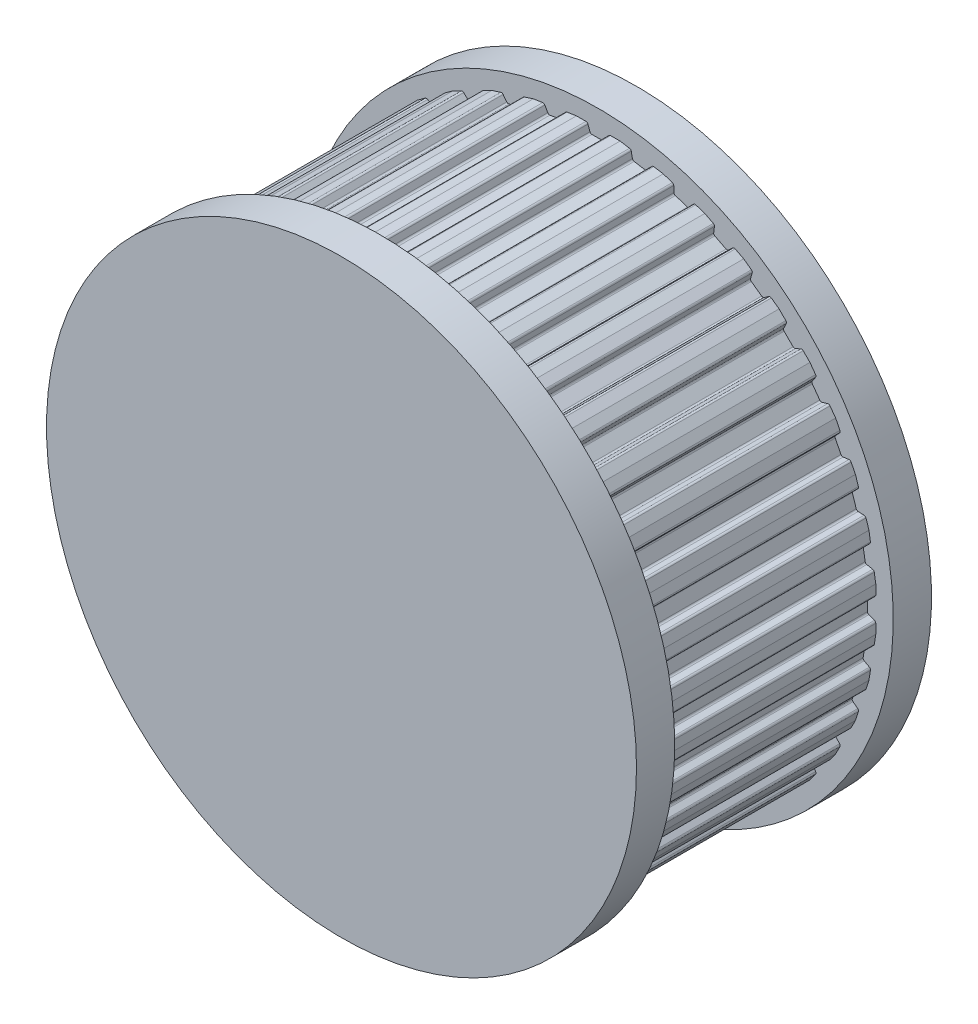
SolidWorks part; units mm, degrees
ref_plane "Front Plane" through (0, 0, 0) normal (0, 0, 1) x (1, 0, 0)
ref_plane "Top Plane" through (0, 0, 0) normal (0, 1, 0) x (1, 0, 0)
ref_plane "Right Plane" through (0, 0, 0) normal (1, 0, 0) x (0, 0, -1)
sketch "Sketch1" plane through (0, 0, 0) normal (0, 0, 1) x (1, 0, 0)
  line L0 (-50.7835, 0) -> (-50.3466, 0)
  line L5 (-50.2571, 0.0627) -> (-50.1641, 0.3183)
  line L6 (-50.0746, 0.381) -> (-49.4934, 0.381)
  line L7 (-49.784, 0.381) -> (-49.784, 0) construction
  line L8 (-49.3109, 0.0627) -> (-49.4039, 0.3183)
  line L39 (-51.2936, 0.1442) -> (-51.3455, 0.4113)
  line L40 (-50.2571, 0.0627) -> (-49.3109, 0.0627) construction
  line L56 (-49.2214, 0) -> (-48.7845, 0)
  line L60 (-51.9981, 0.5781) -> (-51.4241, 0.4872)
  line L61 (-52.2282, 0.2923) -> (-52.0963, 0.5302)
  line L62 (-52.7579, 0.3127) -> (-52.3264, 0.2444)
  line L63 (-51.215, 0.0683) -> (-50.7835, 0)
  line L64 (-53.2392, 0.535) -> (-53.2487, 0.8069)
  line L65 (-53.8671, 1.0737) -> (-53.3144, 0.8941)
  line L66 (-54.1391, 0.8274) -> (-53.9716, 1.0418)
  line L67 (-54.6591, 0.9304) -> (-54.2436, 0.7954)
  line L68 (-53.1734, 0.4477) -> (-52.7579, 0.3127)
  line L69 (-55.0997, 1.2253) -> (-55.0665, 1.4953)
  line L70 (-55.6356, 1.8556) -> (-55.1178, 1.5918)
  line L71 (-55.9428, 1.6549) -> (-55.7438, 1.8404)
  line L72 (-56.4403, 1.838) -> (-56.051, 1.6396)
  line L73 (-55.0484, 1.1288) -> (-54.6591, 0.9304)
  line L74 (-56.8293, 2.1981) -> (-56.7543, 2.4596)
  line L75 (-57.26, 2.9045) -> (-56.7898, 2.5629)
  line L76 (-57.5948, 2.7543) -> (-57.3693, 2.9064)
  line L77 (-58.0575, 3.013) -> (-57.7041, 2.7562)
  line L78 (-56.7937, 2.0948) -> (-56.4403, 1.838)
  line L79 (-58.3854, 3.4295) -> (-58.2704, 3.6761)
  line L80 (-58.7003, 4.1946) -> (-58.2894, 3.7837)
  line L81 (-59.0545, 4.0986) -> (-58.8079, 4.2136)
  line L82 (-59.471, 4.4265) -> (-59.1621, 4.1176)
  line L83 (-58.3664, 3.3219) -> (-58.0575, 3.013)
  line L84 (-59.7297, 4.8892) -> (-59.5776, 5.1147)
  line L85 (-59.9211, 5.6942) -> (-59.5795, 5.224)
  line L86 (-60.2859, 5.6547) -> (-60.0244, 5.7297)
  line L87 (-60.646, 6.0437) -> (-60.3892, 5.6903)
  line L88 (-59.7278, 4.7799) -> (-59.471, 4.4265)
  line L89 (-60.8291, 6.5412) -> (-60.6436, 6.7402)
  line L90 (-60.8922, 7.3662) -> (-60.6284, 6.8484)
  line L91 (-61.2587, 7.3843) -> (-60.9887, 7.4175)
  line L92 (-61.5536, 7.8249) -> (-61.3552, 7.4356)
  line L93 (-60.8444, 6.433) -> (-60.646, 6.0437)
  line L94 (-61.6566, 8.3449) -> (-61.4422, 8.5124)
  line L95 (-61.5899, 9.1696) -> (-61.4103, 8.6169)
  line L96 (-61.949, 9.2448) -> (-61.6771, 9.2353)
  line L97 (-62.1713, 9.7261) -> (-62.0363, 9.3106)
  line L98 (-61.6886, 8.2404) -> (-61.5536, 7.8249)
  line L99 (-62.1917, 10.2558) -> (-61.9538, 10.3877)
  line L100 (-61.9968, 11.0599) -> (-61.9059, 10.4859)
  line L101 (-62.3398, 11.1904) -> (-62.0727, 11.1385)
  line L102 (-62.484, 11.7005) -> (-62.4157, 11.269)
  line L103 (-62.2396, 10.1576) -> (-62.1713, 9.7261)
  line L104 (-62.4213, 12.2269) -> (-62.1657, 12.3199)
  line L105 (-62.103, 12.9906) -> (-62.103, 12.4094)
  line L106 (-62.4213, 13.1731) -> (-62.1657, 13.0801)
  line L107 (-62.484, 13.6995) -> (-62.484, 13.2626)
  line L108 (-62.484, 12.1374) -> (-62.484, 11.7005)
  line L109 (-62.3398, 14.2096) -> (-62.0727, 14.2615)
  line L110 (-61.9059, 14.9141) -> (-61.9968, 14.3401)
  line L111 (-62.1917, 15.1442) -> (-61.9538, 15.0123)
  line L112 (-62.1713, 15.6739) -> (-62.2396, 15.2424)
  line L113 (-62.4157, 14.131) -> (-62.484, 13.6995)
  line L114 (-61.949, 16.1552) -> (-61.6771, 16.1647)
  line L115 (-61.4103, 16.7831) -> (-61.5899, 16.2304)
  line L116 (-61.6566, 17.0551) -> (-61.4422, 16.8876)
  line L117 (-61.5536, 17.5751) -> (-61.6886, 17.1596)
  line L118 (-62.0363, 16.0894) -> (-62.1713, 15.6739)
  line L119 (-61.2587, 18.0157) -> (-60.9887, 17.9825)
  line L120 (-60.6284, 18.5516) -> (-60.8922, 18.0338)
  line L121 (-60.8291, 18.8588) -> (-60.6436, 18.6598)
  line L122 (-60.646, 19.3563) -> (-60.8444, 18.967)
  line L123 (-61.3552, 17.9644) -> (-61.5536, 17.5751)
  line L124 (-60.2859, 19.7453) -> (-60.0244, 19.6703)
  line L125 (-59.5795, 20.176) -> (-59.9211, 19.7058)
  line L126 (-59.7297, 20.5108) -> (-59.5776, 20.2853)
  line L127 (-59.471, 20.9735) -> (-59.7278, 20.6201)
  line L128 (-60.3892, 19.7097) -> (-60.646, 19.3563)
  line L129 (-59.0545, 21.3014) -> (-58.8079, 21.1864)
  line L130 (-58.2894, 21.6163) -> (-58.7003, 21.2054)
  line L131 (-58.3854, 21.9705) -> (-58.2704, 21.7239)
  line L132 (-58.0575, 22.387) -> (-58.3664, 22.0781)
  line L133 (-59.1621, 21.2824) -> (-59.471, 20.9735)
  line L134 (-57.5948, 22.6457) -> (-57.3693, 22.4936)
  line L135 (-56.7898, 22.8371) -> (-57.26, 22.4955)
  line L136 (-56.8293, 23.2019) -> (-56.7543, 22.9404)
  line L137 (-56.4403, 23.562) -> (-56.7937, 23.3052)
  line L138 (-57.7041, 22.6438) -> (-58.0575, 22.387)
  line L139 (-55.9428, 23.7451) -> (-55.7438, 23.5596)
  line L140 (-55.1178, 23.8082) -> (-55.6356, 23.5444)
  line L141 (-55.0997, 24.1747) -> (-55.0665, 23.9047)
  line L142 (-54.6591, 24.4696) -> (-55.0484, 24.2712)
  line L143 (-56.051, 23.7604) -> (-56.4403, 23.562)
  line L144 (-54.1391, 24.5726) -> (-53.9716, 24.3582)
  line L145 (-53.3144, 24.5059) -> (-53.8671, 24.3263)
  line L146 (-53.2392, 24.865) -> (-53.2487, 24.5931)
  line L147 (-52.7579, 25.0873) -> (-53.1734, 24.9523)
  line L148 (-54.2436, 24.6046) -> (-54.6591, 24.4696)
  line L149 (-52.2282, 25.1077) -> (-52.0963, 24.8698)
  line L150 (-51.4241, 24.9128) -> (-51.9981, 24.8219)
  line L151 (-51.2936, 25.2558) -> (-51.3455, 24.9887)
  line L152 (-50.7835, 25.4) -> (-51.215, 25.3317)
  line L153 (-52.3264, 25.1556) -> (-52.7579, 25.0873)
  line L154 (-50.2571, 25.3373) -> (-50.1641, 25.0817)
  line L155 (-49.4934, 25.019) -> (-50.0746, 25.019)
  line L156 (-49.3109, 25.3373) -> (-49.4039, 25.0817)
  line L157 (-48.7845, 25.4) -> (-49.2214, 25.4)
  line L158 (-50.3466, 25.4) -> (-50.7835, 25.4)
  line L159 (-48.2744, 25.2558) -> (-48.2225, 24.9887)
  line L160 (-47.5699, 24.8219) -> (-48.1439, 24.9128)
  line L161 (-47.3398, 25.1077) -> (-47.4717, 24.8698)
  line L162 (-46.8101, 25.0873) -> (-47.2416, 25.1556)
  line L163 (-48.353, 25.3317) -> (-48.7845, 25.4)
  line L164 (-46.3288, 24.865) -> (-46.3193, 24.5931)
  line L165 (-45.7009, 24.3263) -> (-46.2536, 24.5059)
  line L166 (-45.4289, 24.5726) -> (-45.5964, 24.3582)
  line L167 (-44.9089, 24.4696) -> (-45.3244, 24.6046)
  line L168 (-46.3946, 24.9523) -> (-46.8101, 25.0873)
  line L169 (-44.4683, 24.1747) -> (-44.5015, 23.9047)
  line L170 (-43.9324, 23.5444) -> (-44.4502, 23.8082)
  line L171 (-43.6252, 23.7451) -> (-43.8242, 23.5596)
  line L172 (-43.1277, 23.562) -> (-43.517, 23.7604)
  line L173 (-44.5196, 24.2712) -> (-44.9089, 24.4696)
  line L174 (-42.7387, 23.2019) -> (-42.8137, 22.9404)
  line L175 (-42.308, 22.4955) -> (-42.7782, 22.8371)
  line L176 (-41.9732, 22.6457) -> (-42.1987, 22.4936)
  line L177 (-41.5105, 22.387) -> (-41.8639, 22.6438)
  line L178 (-42.7743, 23.3052) -> (-43.1277, 23.562)
  line L179 (-41.1826, 21.9705) -> (-41.2976, 21.7239)
  line L180 (-40.8677, 21.2054) -> (-41.2786, 21.6163)
  line L181 (-40.5135, 21.3014) -> (-40.7601, 21.1864)
  line L182 (-40.097, 20.9735) -> (-40.4059, 21.2824)
  line L183 (-41.2016, 22.0781) -> (-41.5105, 22.387)
  line L184 (-39.8383, 20.5108) -> (-39.9904, 20.2853)
  line L185 (-39.6469, 19.7058) -> (-39.9885, 20.176)
  line L186 (-39.2821, 19.7453) -> (-39.5436, 19.6703)
  line L187 (-38.922, 19.3563) -> (-39.1788, 19.7097)
  line L188 (-39.8402, 20.6201) -> (-40.097, 20.9735)
  line L189 (-38.7389, 18.8588) -> (-38.9244, 18.6598)
  line L190 (-38.6758, 18.0338) -> (-38.9396, 18.5516)
  line L191 (-38.3093, 18.0157) -> (-38.5793, 17.9825)
  line L192 (-38.0144, 17.5751) -> (-38.2128, 17.9644)
  line L193 (-38.7236, 18.967) -> (-38.922, 19.3563)
  line L194 (-37.9114, 17.0551) -> (-38.1258, 16.8876)
  line L195 (-37.9781, 16.2304) -> (-38.1577, 16.7831)
  line L196 (-37.619, 16.1552) -> (-37.8909, 16.1647)
  line L197 (-37.3967, 15.6739) -> (-37.5317, 16.0894)
  line L198 (-37.8794, 17.1596) -> (-38.0144, 17.5751)
  line L199 (-37.3763, 15.1442) -> (-37.6142, 15.0123)
  line L200 (-37.5712, 14.3401) -> (-37.6621, 14.9141)
  line L201 (-37.2282, 14.2096) -> (-37.4953, 14.2615)
  line L202 (-37.084, 13.6995) -> (-37.1523, 14.131)
  line L203 (-37.3284, 15.2424) -> (-37.3967, 15.6739)
  line L204 (-37.1467, 13.1731) -> (-37.4023, 13.0801)
  line L205 (-37.465, 12.4094) -> (-37.465, 12.9906)
  line L206 (-37.1467, 12.2269) -> (-37.4023, 12.3199)
  line L207 (-37.084, 11.7005) -> (-37.084, 12.1374)
  line L208 (-37.084, 13.2626) -> (-37.084, 13.6995)
  line L209 (-37.2282, 11.1904) -> (-37.4953, 11.1385)
  line L210 (-37.6621, 10.4859) -> (-37.5712, 11.0599)
  line L211 (-37.3763, 10.2558) -> (-37.6142, 10.3877)
  line L212 (-37.3967, 9.7261) -> (-37.3284, 10.1576)
  line L213 (-37.1523, 11.269) -> (-37.084, 11.7005)
  line L214 (-37.619, 9.2448) -> (-37.8909, 9.2353)
  line L215 (-38.1577, 8.6169) -> (-37.9781, 9.1696)
  line L216 (-37.9114, 8.3449) -> (-38.1258, 8.5124)
  line L217 (-38.0144, 7.8249) -> (-37.8794, 8.2404)
  line L218 (-37.5317, 9.3106) -> (-37.3967, 9.7261)
  line L219 (-38.3093, 7.3843) -> (-38.5793, 7.4175)
  line L220 (-38.9396, 6.8484) -> (-38.6758, 7.3662)
  line L221 (-38.7389, 6.5412) -> (-38.9244, 6.7402)
  line L222 (-38.922, 6.0437) -> (-38.7236, 6.433)
  line L223 (-38.2128, 7.4356) -> (-38.0144, 7.8249)
  line L224 (-39.2821, 5.6547) -> (-39.5436, 5.7297)
  line L225 (-39.9885, 5.224) -> (-39.6469, 5.6942)
  line L226 (-39.8383, 4.8892) -> (-39.9904, 5.1147)
  line L227 (-40.097, 4.4265) -> (-39.8402, 4.7799)
  line L228 (-39.1788, 5.6903) -> (-38.922, 6.0437)
  line L229 (-40.5135, 4.0986) -> (-40.7601, 4.2136)
  line L230 (-41.2786, 3.7837) -> (-40.8677, 4.1946)
  line L231 (-41.1826, 3.4295) -> (-41.2976, 3.6761)
  line L232 (-41.5105, 3.013) -> (-41.2016, 3.3219)
  line L233 (-40.4059, 4.1176) -> (-40.097, 4.4265)
  line L234 (-41.9732, 2.7543) -> (-42.1987, 2.9064)
  line L235 (-42.7782, 2.5629) -> (-42.308, 2.9045)
  line L236 (-42.7387, 2.1981) -> (-42.8137, 2.4596)
  line L237 (-43.1277, 1.838) -> (-42.7743, 2.0948)
  line L238 (-41.8639, 2.7562) -> (-41.5105, 3.013)
  line L239 (-43.6252, 1.6549) -> (-43.8242, 1.8404)
  line L240 (-44.4502, 1.5918) -> (-43.9324, 1.8556)
  line L241 (-44.4683, 1.2253) -> (-44.5015, 1.4953)
  line L242 (-44.9089, 0.9304) -> (-44.5196, 1.1288)
  line L243 (-43.517, 1.6396) -> (-43.1277, 1.838)
  line L244 (-45.4289, 0.8274) -> (-45.5964, 1.0418)
  line L245 (-46.2536, 0.8941) -> (-45.7009, 1.0737)
  line L246 (-46.3288, 0.535) -> (-46.3193, 0.8069)
  line L247 (-46.8101, 0.3127) -> (-46.3946, 0.4477)
  line L248 (-45.3244, 0.7954) -> (-44.9089, 0.9304)
  line L249 (-47.3398, 0.2923) -> (-47.4717, 0.5302)
  line L250 (-48.1439, 0.4872) -> (-47.5699, 0.5781)
  line L251 (-48.2744, 0.1442) -> (-48.2225, 0.4113)
  line L252 (-48.7845, 0) -> (-48.353, 0.0683)
  line L253 (-47.2416, 0.2444) -> (-46.8101, 0.3127)
  arc A0 (-50.3466, 0) -> (-50.2571, 0.0627) centre (-50.3466, 0.0952) ccw
  arc A1 (-50.1641, 0.3183) -> (-50.0746, 0.381) centre (-50.0746, 0.2857) cw
  arc A2 (-49.4039, 0.3183) -> (-49.4934, 0.381) centre (-49.4934, 0.2857) ccw
  arc A3 (-49.2214, 0) -> (-49.3109, 0.0627) centre (-49.2214, 0.0952) cw
  arc A4 (-51.215, 0.0683) -> (-51.2936, 0.1442) centre (-51.2001, 0.1624) cw
  arc A5 (-51.3455, 0.4113) -> (-51.4241, 0.4872) centre (-51.439, 0.3931) ccw
  arc A6 (-52.0963, 0.5302) -> (-51.9981, 0.5781) centre (-52.013, 0.484) cw
  arc A7 (-52.3264, 0.2444) -> (-52.2282, 0.2923) centre (-52.3115, 0.3385) ccw
  arc A8 (-53.1734, 0.4477) -> (-53.2392, 0.535) centre (-53.144, 0.5383) cw
  arc A9 (-53.2487, 0.8069) -> (-53.3144, 0.8941) centre (-53.3439, 0.8036) ccw
  arc A10 (-53.9716, 1.0418) -> (-53.8671, 1.0737) centre (-53.8966, 0.9831) cw
  arc A11 (-54.2436, 0.7954) -> (-54.1391, 0.8274) centre (-54.2142, 0.886) ccw
  arc A12 (-55.0484, 1.1288) -> (-55.0997, 1.2253) centre (-55.0051, 1.2137) cw
  arc A13 (-55.0665, 1.4953) -> (-55.1178, 1.5918) centre (-55.1611, 1.5069) ccw
  arc A14 (-55.7438, 1.8404) -> (-55.6356, 1.8556) centre (-55.6789, 1.7707) cw
  arc A15 (-56.051, 1.6396) -> (-55.9428, 1.6549) centre (-56.0077, 1.7245) ccw
  arc A16 (-56.7937, 2.0948) -> (-56.8293, 2.1981) centre (-56.7377, 2.1718) cw
  arc A17 (-56.7543, 2.4596) -> (-56.7898, 2.5629) centre (-56.8458, 2.4859) ccw
  arc A18 (-57.3693, 2.9064) -> (-57.26, 2.9045) centre (-57.316, 2.8275) cw
  arc A19 (-57.7041, 2.7562) -> (-57.5948, 2.7543) centre (-57.6481, 2.8333) ccw
  arc A20 (-58.3664, 3.3219) -> (-58.3854, 3.4295) centre (-58.2991, 3.3893) cw
  arc A21 (-58.2704, 3.6761) -> (-58.2894, 3.7837) centre (-58.3567, 3.7163) ccw
  arc A22 (-58.8079, 4.2136) -> (-58.7003, 4.1946) centre (-58.7677, 4.1273) cw
  arc A23 (-59.1621, 4.1176) -> (-59.0545, 4.0986) centre (-59.0947, 4.1849) ccw
  arc A24 (-59.7278, 4.7799) -> (-59.7297, 4.8892) centre (-59.6507, 4.8359) cw
  arc A25 (-59.5776, 5.1147) -> (-59.5795, 5.224) centre (-59.6565, 5.168) ccw
  arc A26 (-60.0244, 5.7297) -> (-59.9211, 5.6942) centre (-59.9981, 5.6382) cw
  arc A27 (-60.3892, 5.6903) -> (-60.2859, 5.6547) centre (-60.3122, 5.7463) ccw
  arc A28 (-60.8444, 6.433) -> (-60.8291, 6.5412) centre (-60.7595, 6.4763) cw
  arc A29 (-60.6436, 6.7402) -> (-60.6284, 6.8484) centre (-60.7133, 6.8051) ccw
  arc A30 (-60.9887, 7.4175) -> (-60.8922, 7.3662) centre (-60.9771, 7.3229) cw
  arc A31 (-61.3552, 7.4356) -> (-61.2587, 7.3843) centre (-61.2703, 7.4789) ccw
  arc A32 (-61.6886, 8.2404) -> (-61.6566, 8.3449) centre (-61.598, 8.2698) cw
  arc A33 (-61.4422, 8.5124) -> (-61.4103, 8.6169) centre (-61.5009, 8.5874) ccw
  arc A34 (-61.6771, 9.2353) -> (-61.5899, 9.1696) centre (-61.6804, 9.1401) cw
  arc A35 (-62.0363, 9.3106) -> (-61.949, 9.2448) centre (-61.9457, 9.34) ccw
  arc A36 (-62.2396, 10.1576) -> (-62.1917, 10.2558) centre (-62.1455, 10.1725) cw
  arc A37 (-61.9538, 10.3877) -> (-61.9059, 10.4859) centre (-62, 10.471) ccw
  arc A38 (-62.0727, 11.1385) -> (-61.9968, 11.0599) centre (-62.0909, 11.045) cw
  arc A39 (-62.4157, 11.269) -> (-62.3398, 11.1904) centre (-62.3216, 11.2839) ccw
  arc A40 (-62.484, 12.1374) -> (-62.4213, 12.2269) centre (-62.3888, 12.1374) cw
  arc A41 (-62.1657, 12.3199) -> (-62.103, 12.4094) centre (-62.1983, 12.4094) ccw
  arc A42 (-62.1657, 13.0801) -> (-62.103, 12.9906) centre (-62.1983, 12.9906) cw
  arc A43 (-62.484, 13.2626) -> (-62.4213, 13.1731) centre (-62.3888, 13.2626) ccw
  arc A44 (-62.4157, 14.131) -> (-62.3398, 14.2096) centre (-62.3216, 14.1161) cw
  arc A45 (-62.0727, 14.2615) -> (-61.9968, 14.3401) centre (-62.0909, 14.355) ccw
  arc A46 (-61.9538, 15.0123) -> (-61.9059, 14.9141) centre (-62, 14.929) cw
  arc A47 (-62.2396, 15.2424) -> (-62.1917, 15.1442) centre (-62.1455, 15.2275) ccw
  arc A48 (-62.0363, 16.0894) -> (-61.949, 16.1552) centre (-61.9457, 16.06) cw
  arc A49 (-61.6771, 16.1647) -> (-61.5899, 16.2304) centre (-61.6804, 16.2599) ccw
  arc A50 (-61.4422, 16.8876) -> (-61.4103, 16.7831) centre (-61.5009, 16.8126) cw
  arc A51 (-61.6886, 17.1596) -> (-61.6566, 17.0551) centre (-61.598, 17.1302) ccw
  arc A52 (-61.3552, 17.9644) -> (-61.2587, 18.0157) centre (-61.2703, 17.9211) cw
  arc A53 (-60.9887, 17.9825) -> (-60.8922, 18.0338) centre (-60.9771, 18.0771) ccw
  arc A54 (-60.6436, 18.6598) -> (-60.6284, 18.5516) centre (-60.7133, 18.5949) cw
  arc A55 (-60.8444, 18.967) -> (-60.8291, 18.8588) centre (-60.7595, 18.9237) ccw
  arc A56 (-60.3892, 19.7097) -> (-60.2859, 19.7453) centre (-60.3122, 19.6537) cw
  arc A57 (-60.0244, 19.6703) -> (-59.9211, 19.7058) centre (-59.9981, 19.7618) ccw
  arc A58 (-59.5776, 20.2853) -> (-59.5795, 20.176) centre (-59.6565, 20.232) cw
  arc A59 (-59.7278, 20.6201) -> (-59.7297, 20.5108) centre (-59.6507, 20.5641) ccw
  arc A60 (-59.1621, 21.2824) -> (-59.0545, 21.3014) centre (-59.0947, 21.2151) cw
  arc A61 (-58.8079, 21.1864) -> (-58.7003, 21.2054) centre (-58.7677, 21.2727) ccw
  arc A62 (-58.2704, 21.7239) -> (-58.2894, 21.6163) centre (-58.3567, 21.6837) cw
  arc A63 (-58.3664, 22.0781) -> (-58.3854, 21.9705) centre (-58.2991, 22.0107) ccw
  arc A64 (-57.7041, 22.6438) -> (-57.5948, 22.6457) centre (-57.6481, 22.5667) cw
  arc A65 (-57.3693, 22.4936) -> (-57.26, 22.4955) centre (-57.316, 22.5725) ccw
  arc A66 (-56.7543, 22.9404) -> (-56.7898, 22.8371) centre (-56.8458, 22.9141) cw
  arc A67 (-56.7937, 23.3052) -> (-56.8293, 23.2019) centre (-56.7377, 23.2282) ccw
  arc A68 (-56.051, 23.7604) -> (-55.9428, 23.7451) centre (-56.0077, 23.6755) cw
  arc A69 (-55.7438, 23.5596) -> (-55.6356, 23.5444) centre (-55.6789, 23.6293) ccw
  arc A70 (-55.0665, 23.9047) -> (-55.1178, 23.8082) centre (-55.1611, 23.8931) cw
  arc A71 (-55.0484, 24.2712) -> (-55.0997, 24.1747) centre (-55.0051, 24.1863) ccw
  arc A72 (-54.2436, 24.6046) -> (-54.1391, 24.5726) centre (-54.2142, 24.514) cw
  arc A73 (-53.9716, 24.3582) -> (-53.8671, 24.3263) centre (-53.8966, 24.4169) ccw
  arc A74 (-53.2487, 24.5931) -> (-53.3144, 24.5059) centre (-53.3439, 24.5964) cw
  arc A75 (-53.1734, 24.9523) -> (-53.2392, 24.865) centre (-53.144, 24.8617) ccw
  arc A76 (-52.3264, 25.1556) -> (-52.2282, 25.1077) centre (-52.3115, 25.0615) cw
  arc A77 (-52.0963, 24.8698) -> (-51.9981, 24.8219) centre (-52.013, 24.916) ccw
  arc A78 (-51.3455, 24.9887) -> (-51.4241, 24.9128) centre (-51.439, 25.0069) cw
  arc A79 (-51.215, 25.3317) -> (-51.2936, 25.2558) centre (-51.2001, 25.2376) ccw
  arc A80 (-50.3466, 25.4) -> (-50.2571, 25.3373) centre (-50.3466, 25.3048) cw
  arc A81 (-50.1641, 25.0817) -> (-50.0746, 25.019) centre (-50.0746, 25.1143) ccw
  arc A82 (-49.4039, 25.0817) -> (-49.4934, 25.019) centre (-49.4934, 25.1143) cw
  arc A83 (-49.2214, 25.4) -> (-49.3109, 25.3373) centre (-49.2214, 25.3048) ccw
  arc A84 (-48.353, 25.3317) -> (-48.2744, 25.2558) centre (-48.3679, 25.2376) cw
  arc A85 (-48.2225, 24.9887) -> (-48.1439, 24.9128) centre (-48.129, 25.0069) ccw
  arc A86 (-47.4717, 24.8698) -> (-47.5699, 24.8219) centre (-47.555, 24.916) cw
  arc A87 (-47.2416, 25.1556) -> (-47.3398, 25.1077) centre (-47.2565, 25.0615) ccw
  arc A88 (-46.3946, 24.9523) -> (-46.3288, 24.865) centre (-46.424, 24.8617) cw
  arc A89 (-46.3193, 24.5931) -> (-46.2536, 24.5059) centre (-46.2241, 24.5964) ccw
  arc A90 (-45.5964, 24.3582) -> (-45.7009, 24.3263) centre (-45.6714, 24.4169) cw
  arc A91 (-45.3244, 24.6046) -> (-45.4289, 24.5726) centre (-45.3538, 24.514) ccw
  arc A92 (-44.5196, 24.2712) -> (-44.4683, 24.1747) centre (-44.5629, 24.1863) cw
  arc A93 (-44.5015, 23.9047) -> (-44.4502, 23.8082) centre (-44.4069, 23.8931) ccw
  arc A94 (-43.8242, 23.5596) -> (-43.9324, 23.5444) centre (-43.8891, 23.6293) cw
  arc A95 (-43.517, 23.7604) -> (-43.6252, 23.7451) centre (-43.5603, 23.6755) ccw
  arc A96 (-42.7743, 23.3052) -> (-42.7387, 23.2019) centre (-42.8303, 23.2282) cw
  arc A97 (-42.8137, 22.9404) -> (-42.7782, 22.8371) centre (-42.7222, 22.9141) ccw
  arc A98 (-42.1987, 22.4936) -> (-42.308, 22.4955) centre (-42.252, 22.5725) cw
  arc A99 (-41.8639, 22.6438) -> (-41.9732, 22.6457) centre (-41.9199, 22.5667) ccw
  arc A100 (-41.2016, 22.0781) -> (-41.1826, 21.9705) centre (-41.2689, 22.0107) cw
  arc A101 (-41.2976, 21.7239) -> (-41.2786, 21.6163) centre (-41.2113, 21.6837) ccw
  arc A102 (-40.7601, 21.1864) -> (-40.8677, 21.2054) centre (-40.8003, 21.2727) cw
  arc A103 (-40.4059, 21.2824) -> (-40.5135, 21.3014) centre (-40.4733, 21.2151) ccw
  arc A104 (-39.8402, 20.6201) -> (-39.8383, 20.5108) centre (-39.9173, 20.5641) cw
  arc A105 (-39.9904, 20.2853) -> (-39.9885, 20.176) centre (-39.9115, 20.232) ccw
  arc A106 (-39.5436, 19.6703) -> (-39.6469, 19.7058) centre (-39.5699, 19.7618) cw
  arc A107 (-39.1788, 19.7097) -> (-39.2821, 19.7453) centre (-39.2558, 19.6537) ccw
  arc A108 (-38.7236, 18.967) -> (-38.7389, 18.8588) centre (-38.8085, 18.9237) cw
  arc A109 (-38.9244, 18.6598) -> (-38.9396, 18.5516) centre (-38.8547, 18.5949) ccw
  arc A110 (-38.5793, 17.9825) -> (-38.6758, 18.0338) centre (-38.5909, 18.0771) cw
  arc A111 (-38.2128, 17.9644) -> (-38.3093, 18.0157) centre (-38.2977, 17.9211) ccw
  arc A112 (-37.8794, 17.1596) -> (-37.9114, 17.0551) centre (-37.97, 17.1302) cw
  arc A113 (-38.1258, 16.8876) -> (-38.1577, 16.7831) centre (-38.0671, 16.8126) ccw
  arc A114 (-37.8909, 16.1647) -> (-37.9781, 16.2304) centre (-37.8876, 16.2599) cw
  arc A115 (-37.5317, 16.0894) -> (-37.619, 16.1552) centre (-37.6223, 16.06) ccw
  arc A116 (-37.3284, 15.2424) -> (-37.3763, 15.1442) centre (-37.4225, 15.2275) cw
  arc A117 (-37.6142, 15.0123) -> (-37.6621, 14.9141) centre (-37.568, 14.929) ccw
  arc A118 (-37.4953, 14.2615) -> (-37.5712, 14.3401) centre (-37.4771, 14.355) cw
  arc A119 (-37.1523, 14.131) -> (-37.2282, 14.2096) centre (-37.2464, 14.1161) ccw
  arc A120 (-37.084, 13.2626) -> (-37.1467, 13.1731) centre (-37.1792, 13.2626) cw
  arc A121 (-37.4023, 13.0801) -> (-37.465, 12.9906) centre (-37.3697, 12.9906) ccw
  arc A122 (-37.4023, 12.3199) -> (-37.465, 12.4094) centre (-37.3698, 12.4094) cw
  arc A123 (-37.084, 12.1374) -> (-37.1467, 12.2269) centre (-37.1792, 12.1374) ccw
  arc A124 (-37.1523, 11.269) -> (-37.2282, 11.1904) centre (-37.2464, 11.2839) cw
  arc A125 (-37.4953, 11.1385) -> (-37.5712, 11.0599) centre (-37.4771, 11.045) ccw
  arc A126 (-37.6142, 10.3877) -> (-37.6621, 10.4859) centre (-37.568, 10.471) cw
  arc A127 (-37.3284, 10.1576) -> (-37.3763, 10.2558) centre (-37.4225, 10.1725) ccw
  arc A128 (-37.5317, 9.3106) -> (-37.619, 9.2448) centre (-37.6223, 9.34) cw
  arc A129 (-37.8909, 9.2353) -> (-37.9781, 9.1696) centre (-37.8876, 9.1401) ccw
  arc A130 (-38.1258, 8.5124) -> (-38.1577, 8.6169) centre (-38.0671, 8.5874) cw
  arc A131 (-37.8794, 8.2404) -> (-37.9114, 8.3449) centre (-37.97, 8.2698) ccw
  arc A132 (-38.2128, 7.4356) -> (-38.3093, 7.3843) centre (-38.2977, 7.4789) cw
  arc A133 (-38.5793, 7.4175) -> (-38.6758, 7.3662) centre (-38.5909, 7.3229) ccw
  arc A134 (-38.9244, 6.7402) -> (-38.9396, 6.8484) centre (-38.8547, 6.8051) cw
  arc A135 (-38.7236, 6.433) -> (-38.7389, 6.5412) centre (-38.8085, 6.4763) ccw
  arc A136 (-39.1788, 5.6903) -> (-39.2821, 5.6547) centre (-39.2558, 5.7463) cw
  arc A137 (-39.5436, 5.7297) -> (-39.6469, 5.6942) centre (-39.5699, 5.6382) ccw
  arc A138 (-39.9904, 5.1147) -> (-39.9885, 5.224) centre (-39.9115, 5.168) cw
  arc A139 (-39.8402, 4.7799) -> (-39.8383, 4.8892) centre (-39.9173, 4.8359) ccw
  arc A140 (-40.4059, 4.1176) -> (-40.5135, 4.0986) centre (-40.4733, 4.1849) cw
  arc A141 (-40.7601, 4.2136) -> (-40.8677, 4.1946) centre (-40.8003, 4.1273) ccw
  arc A142 (-41.2976, 3.6761) -> (-41.2786, 3.7837) centre (-41.2113, 3.7163) cw
  arc A143 (-41.2016, 3.3219) -> (-41.1826, 3.4295) centre (-41.2689, 3.3893) ccw
  arc A144 (-41.8639, 2.7562) -> (-41.9732, 2.7543) centre (-41.9199, 2.8333) cw
  arc A145 (-42.1987, 2.9064) -> (-42.308, 2.9045) centre (-42.252, 2.8275) ccw
  arc A146 (-42.8137, 2.4596) -> (-42.7782, 2.5629) centre (-42.7222, 2.4859) cw
  arc A147 (-42.7743, 2.0948) -> (-42.7387, 2.1981) centre (-42.8303, 2.1718) ccw
  arc A148 (-43.517, 1.6396) -> (-43.6252, 1.6549) centre (-43.5603, 1.7245) cw
  arc A149 (-43.8242, 1.8404) -> (-43.9324, 1.8556) centre (-43.8891, 1.7707) ccw
  arc A150 (-44.5015, 1.4953) -> (-44.4502, 1.5918) centre (-44.4069, 1.5069) cw
  arc A151 (-44.5196, 1.1288) -> (-44.4683, 1.2253) centre (-44.5629, 1.2137) ccw
  arc A152 (-45.3244, 0.7954) -> (-45.4289, 0.8274) centre (-45.3538, 0.886) cw
  arc A153 (-45.5964, 1.0418) -> (-45.7009, 1.0737) centre (-45.6714, 0.9831) ccw
  arc A154 (-46.3193, 0.8069) -> (-46.2536, 0.8941) centre (-46.2241, 0.8036) cw
  arc A155 (-46.3946, 0.4477) -> (-46.3288, 0.535) centre (-46.424, 0.5383) ccw
  arc A156 (-47.2416, 0.2444) -> (-47.3398, 0.2923) centre (-47.2565, 0.3385) cw
  arc A157 (-47.4717, 0.5302) -> (-47.5699, 0.5781) centre (-47.555, 0.484) ccw
  arc A158 (-48.2225, 0.4113) -> (-48.1439, 0.4872) centre (-48.129, 0.3931) cw
  arc A159 (-48.353, 0.0683) -> (-48.2744, 0.1442) centre (-48.3679, 0.1624) ccw
  point P1 (-50.292, 0.0172)
  point P2 (-49.784, 12.7)
  point P7 (-49.276, 0.0172)
  point P570 (-49.784, 12.7)
  dimension "D1" = 0.0953
  dimension "D2" = 40
  dimension "D3" = 40
  dimension "D4" = 1.016
  dimension "D7" = 0.381
sketch "Sketch2" plane through (0, 0, 0) normal (0, 0, 1) x (1, 0, 0)
  point P0 (-49.784, 12.7)
  point P1 (0, 0)
extrude "Boss-Extrude1" add sketch "Sketch1" along normal blind 10
sketch "Sketch3" plane through (0, 0, 10) normal (0, 0, 1) x (1, 0, 0)
  circle A0 centre (-49.784, 12.7) radius 13.5
extrude "Boss-Extrude2" add sketch "Sketch3" along normal blind 1.75
sketch "Sketch4" plane through (0, 0, 0) normal (0, 0, -1) x (-1, 0, 0)
  circle A0 centre (49.784, 12.7) radius 13.5
extrude "Boss-Extrude3" add sketch "Sketch4" along normal blind 1.75
